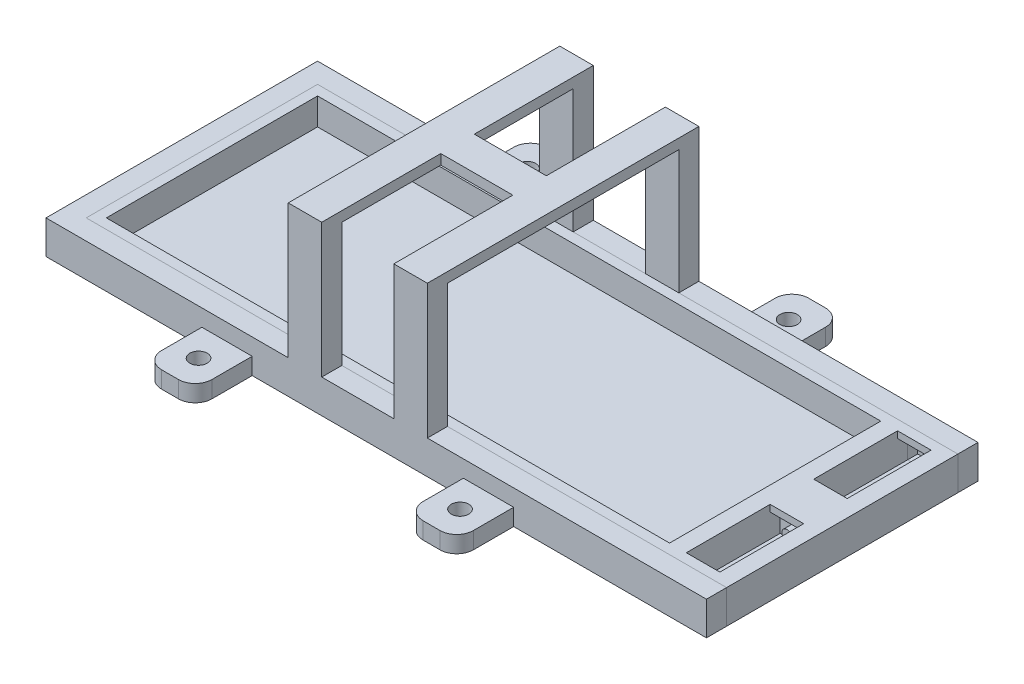
SolidWorks part; units mm, degrees
other "Tray"
other "Cage"
ref_plane "Front Plane" through (0, 0, 0) normal (0, 0, 1) x (1, 0, 0)
ref_plane "Top Plane" through (0, 0, 0) normal (0, 1, 0) x (1, 0, 0)
ref_plane "Right Plane" through (0, 0, 0) normal (1, 0, 0) x (0, 0, -1)
sketch "Sketch1" plane through (0, 0, 0) normal (0, 1, 0) x (1, 0, 0)
  line L0 (-84, 0) -> (-87, 0) construction
  line L1 (-84, -31.5) -> (84, -31.5)
  line L2 (-84, -31.5) -> (-84, 31.5)
  line L3 (-84, 31.5) -> (84, 31.5)
  line L4 (84, -31.5) -> (84, 31.5)
  line L5 (-84, -31.5) -> (84, 31.5) construction
  line L6 (-84, 31.5) -> (84, -31.5) construction
  line L7 (0, 31.5) -> (0, 34.5) construction
  line L8 (0, -31.5) -> (0, -34.5) construction
  line L9 (0, 34.5) -> (-87, 34.5)
  line L10 (-87, 34.5) -> (-87, -34.5)
  line L11 (-87, -34.5) -> (84, -34.5)
  line L12 (0, 34.5) -> (84, 34.5)
  line L13 (84, -34.5) -> (104, -34.5)
  line L14 (84, 34.5) -> (104, 34.5)
  line L15 (104, 34.5) -> (104, -34.5)
  point P0 (0, 0)
  dimension "D1" = 168
  dimension "D2" = 63
  dimension "D3" = 3
  dimension "D4" = 20
  dimension "D5" = 171
extrude "Boss-Extrude1" add sketch "Sketch1" along normal blind 10
sketch "Sketch2" plane through (0, 0, 0) normal (0, 1, 0) x (1, 0, 0)
  line L1 (-84, -31.5) -> (84, -31.5)
  line L2 (-84, -31.5) -> (-84, 31.5)
  line L3 (-84, 31.5) -> (84, 31.5)
  line L4 (84, -31.5) -> (84, 31.5)
  line L5 (-84, -31.5) -> (84, 31.5) construction
  line L6 (-84, 31.5) -> (84, -31.5) construction
  point P0 (0, 0)
extrude "Boss-Extrude2" add sketch "Sketch2" along normal blind 2
sketch "Sketch3" plane through (0, 10, 0) normal (0, 1, 0) x (1, 0, 0)
  line L0 (84, 31.5) -> (104, 31.5) construction
  line L1 (104, -34.5) -> (104, 34.5) construction
  line L2 (94, 31.5) -> (94, 6.5) construction
  line L3 (104, 0) -> (84, 0) construction
  line L4 (84, -31.5) -> (84, 31.5) construction
  line L5 (89, 6.5) -> (99, 6.5)
  line L6 (89, 6.5) -> (89, 31.5)
  line L7 (89, 31.5) -> (99, 31.5)
  line L8 (99, 31.5) -> (99, 6.5)
  point P14 (94, 6.5)
  dimension "D1" = 25
  dimension "D2" = 10
extrude "Cut-Extrude1" cut sketch "Sketch3" against normal through all
mirror "Mirror1" about plane through (0, 0, 0) normal (0, 0, 1) of "Cut-Extrude1"
sketch "Sketch4" plane through (0, 0, 6.5) normal (0, 0, 1) x (1, 0, 0)
  line L0 (89, 0) -> (99, 0)
  line L1 (89, 0) -> (99, 0) construction
  line L2 (94, 10) -> (94, 8) construction
  line L3 (89, 10) -> (99, 10) construction
  line L4 (99, 8) -> (89, 8)
  line L5 (89, 8) -> (89, 0)
  line L6 (99, 8) -> (99, 0)
  point P5 (94, 0)
  point P12 (94, 8)
  dimension "D1" = 10
  dimension "D2" = 2
  dimension "D3" = 8
extrude "Cut-Extrude2" cut sketch "Sketch4" against normal blind 3 and the other way up to next
mirror "Mirror2" about plane through (0, 0, 0) normal (0, 0, 1) of "Cut-Extrude2"
sketch "Sketch6" plane through (0, 0, 3.5) normal (0, 0, 1) x (1, 0, 0)
  line L0 (89, 0) -> (89, 1)
  line L1 (89, 8) -> (89, 0) construction
  line L2 (89, 1) -> (99, 1)
  line L3 (99, 8) -> (99, 0) construction
  line L4 (99, 1) -> (99, 0)
  line L5 (99, 0) -> (89, 0)
  dimension "D1" = 1
extrude "Boss-Extrude4" add sketch "Sketch6" along normal blind 31
mirror "Mirror5" about plane through (0, 0, 0) normal (0, 0, 1) of "Boss-Extrude4"
sketch "Sketch7" plane through (0, 0, 3.5) normal (0, 0, 1) x (1, 0, 0)
  line L0 (94, 8) -> (94, 1) construction
  line L1 (89, 8) -> (99, 8) construction
  line L2 (99, 1) -> (89, 1) construction
  circle A0 centre (94, 4.5) radius 1.5
  dimension "D1" = 3
extrude "Boss-Extrude5" add sketch "Sketch7" along normal blind 3
mirror "Mirror6" about plane through (0, 0, 0) normal (0, 0, 1) of "Boss-Extrude5"
sketch "Sketch8" plane through (0, 0, 0) normal (0, 1, 0) x (1, 0, 0)
  line L0 (104, -34.5) -> (104, 34.5) construction
  line L1 (-87, -34.5) -> (104, -34.5) construction
  line L2 (-87, 34.5) -> (-87, -34.5) construction
  line L3 (104, 34.5) -> (-87, 34.5) construction
  line L4 (104, -34.5) -> (104, 34.5)
  line L5 (-87, -34.5) -> (104, -34.5)
  line L6 (-87, 34.5) -> (-87, -34.5)
  line L7 (104, 34.5) -> (-87, 34.5)
  line L9 (-93, 40.5) -> (-93, -40.5)
  line L12 (110, -40.5) -> (110, 40.5) construction
  line L13 (-93, -40.5) -> (110, -40.5) construction
  line L14 (110, 40.5) -> (-93, 40.5) construction
  line L15 (-93, 40.5) -> (104, 40.5)
  line L16 (-93, -40.5) -> (104, -40.5)
  line L17 (104, 34.5) -> (104, 40.5)
  line L18 (104, -34.5) -> (104, -40.5)
  dimension "D1" = 6
extrude "Boss-Extrude6" add sketch "Sketch8" along normal blind 10 separate body contours L18 L5 L6 L7 L17 L15 L9 L16
sketch "Sketch15" plane through (0, 0, 34.5) normal (0, 0, -1) x (-1, 0, 0)
  line L1 (-89, 8) -> (-99, 8)
  line L2 (-89, 8) -> (-89, 1)
  line L3 (-89, 1) -> (-99, 1)
  line L4 (-99, 8) -> (-99, 1)
sketch "Sketch16" plane through (-87, 0, 0) normal (1, 0, 0) x (0, 0, -1)
  line L0 (5.25, 0) -> (-5.25, 0)
  line L1 (34.5, 0) -> (-34.5, 0) construction
  line L2 (-5.25, 0) -> (-5.25, 5.5)
  line L3 (-5.25, 5.5) -> (5.25, 5.5)
  line L4 (5.25, 5.5) -> (5.25, 0)
  point P6 (0, 0)
  dimension "D1" = 10.5
  dimension "D2" = 5.5
extrude "Cut-Extrude5" cut sketch "Sketch16" against normal blind 3
extrude "Cut-Extrude6" cut sketch "Sketch15" against normal blind 3
mirror "Mirror7" about plane through (0, 0, 0) normal (0, 0, 1) of "Cut-Extrude6"
sketch "Sketch17" plane through (0, 0, 40.5) normal (0, 0, 1) x (1, 0, 0)
  line L0 (39, 0) -> (-39, 0) construction
  line L1 (-93, 0) -> (104, 0) construction
  line L2 (-31.5, 0) -> (-46.5, 0)
  line L3 (46.5, 0) -> (31.5, 0)
  line L4 (-46.5, 0) -> (-46.5, 5)
  line L5 (-46.5, 5) -> (-31.5, 5)
  line L6 (-31.5, 5) -> (-31.5, 0)
  line L7 (31.5, 0) -> (31.5, 5)
  line L8 (31.5, 5) -> (46.5, 5)
  line L9 (46.5, 5) -> (46.5, 0)
  point P6 (0, 0)
  point P10 (-39, 0)
  point P13 (39, 0)
  dimension "D1" = 78
  dimension "D2" = 15
  dimension "D3" = 15
  dimension "D4" = 5
extrude "Boss-Extrude7" add sketch "Sketch17" along normal blind 17
sketch "Sketch18" plane through (0, 5, 0) normal (0, 1, 0) x (1, 0, 0)
  line L0 (-39, -40.5) -> (-39, -57.5) construction
  line L1 (-31.5, -40.5) -> (-46.5, -40.5) construction
  line L2 (-31.5, -57.5) -> (-46.5, -57.5) construction
  line L3 (39, -40.5) -> (39, -57.5) construction
  line L4 (46.5, -40.5) -> (31.5, -40.5) construction
  line L5 (46.5, -57.5) -> (31.5, -57.5) construction
  circle A0 centre (-39, -49) radius 2.6
  circle A1 centre (39, -49) radius 2.6
  dimension "D1" = 5.2
extrude "Cut-Extrude7" cut sketch "Sketch18" against normal up to next (5 mm away)
fillet "Fillet1" radius 5 4 edges at (31.5, 2.5, 57.5) (46.5, 2.5, 57.5) (-46.5, 2.5, 57.5) (-31.5, 2.5, 57.5)
mirror "Mirror8" about plane through (0, 0, 0) normal (0, 0, 1) of "Fillet1", "Cut-Extrude7", "Boss-Extrude7"
sketch "Sketch19" plane through (0, 10, 0) normal (0, 1, 0) x (1, 0, 0)
  line L0 (31.5, -52.5) -> (31.5, -40.5) construction
  line L1 (-31.5, -52.5) -> (-31.5, -40.5) construction
  line L2 (-93, -40.5) -> (104, -40.5) construction
  line L3 (31.5, -52.5) -> (31.5, -40.5) construction
  line L4 (-31.5, -52.5) -> (-31.5, -40.5) construction
  line L5 (-93, -40.5) -> (104, -40.5) construction
  line L6 (-31.5, -46.5) -> (31.5, -46.5) construction
  line L7 (0, -46.5) -> (0, -40.5) construction
  line L8 (-31.5, -40.5) -> (0, -40.5)
  line L9 (0, -40.5) -> (31.5, -40.5)
  line L10 (-15.75, -40.5) -> (-15.75, -34.5) construction
  line L11 (-87, -34.5) -> (104, -34.5) construction
  line L12 (15.75, -40.5) -> (15.75, -34.5) construction
  line L13 (-10.75, -34.5) -> (-20.75, -34.5)
  line L14 (20.75, -34.5) -> (10.75, -34.5)
  line L15 (-20.75, -34.5) -> (-20.75, -40.5)
  line L16 (-20.75, -40.5) -> (-10.75, -40.5)
  line L17 (-10.75, -40.5) -> (-10.75, -34.5)
  line L18 (10.75, -34.5) -> (10.75, -40.5)
  line L19 (10.75, -40.5) -> (20.75, -40.5)
  line L20 (20.75, -40.5) -> (20.75, -34.5)
  circle A0 centre (0, -46.5) radius 2.6 construction
  point P21 (-15.75, -34.5)
  point P24 (15.75, -34.5)
  line M6 (104, -34.5) -> (-87, -34.5)
  dimension "D1" = 5.2
  dimension "D2" = 10
  dimension "D3" = 10
extrude "Boss-Extrude8" add sketch "Sketch19" along normal blind 40 contours L8 L17 L15 M6 | L9 L20 L18 M6
mirror "Mirror9" about plane through (0, 0, 0) normal (0, 0, 1) of "Boss-Extrude8"
sketch "Sketch20" plane through (0, 0, 34.5) normal (0, 0, -1) x (-1, 0, 0)
  line L0 (-10.75, 50) -> (-10.75, 10) construction
  line L1 (-20.75, 50) -> (-10.75, 50)
  line L2 (-20.75, 50) -> (-20.75, 47)
  line L3 (-20.75, 47) -> (-10.75, 47)
  line L4 (-10.75, 50) -> (-10.75, 47)
  dimension "D1" = 3
extrude "Boss-Extrude9" add sketch "Sketch20" along normal up to next
mirror "Mirror10" about plane through (0, 0, 0) normal (1, 0, 0) of "Boss-Extrude9"
sketch "Sketch21" plane through (-10.75, 0, 0) normal (1, 0, 0) x (0, 0, -1)
  line L0 (0, 50) -> (0, 47) construction
  line L1 (-40.5, 50) -> (40.5, 50) construction
  line L2 (34.5, 47) -> (-34.5, 47) construction
  line L3 (5, 50) -> (-5, 50)
  line L4 (-5, 50) -> (-5, 47)
  line L5 (-5, 47) -> (5, 47)
  line L6 (5, 47) -> (5, 50)
  point P9 (0, 50)
  dimension "D1" = 10
extrude "Boss-Extrude10" add sketch "Sketch21" along normal up to next
